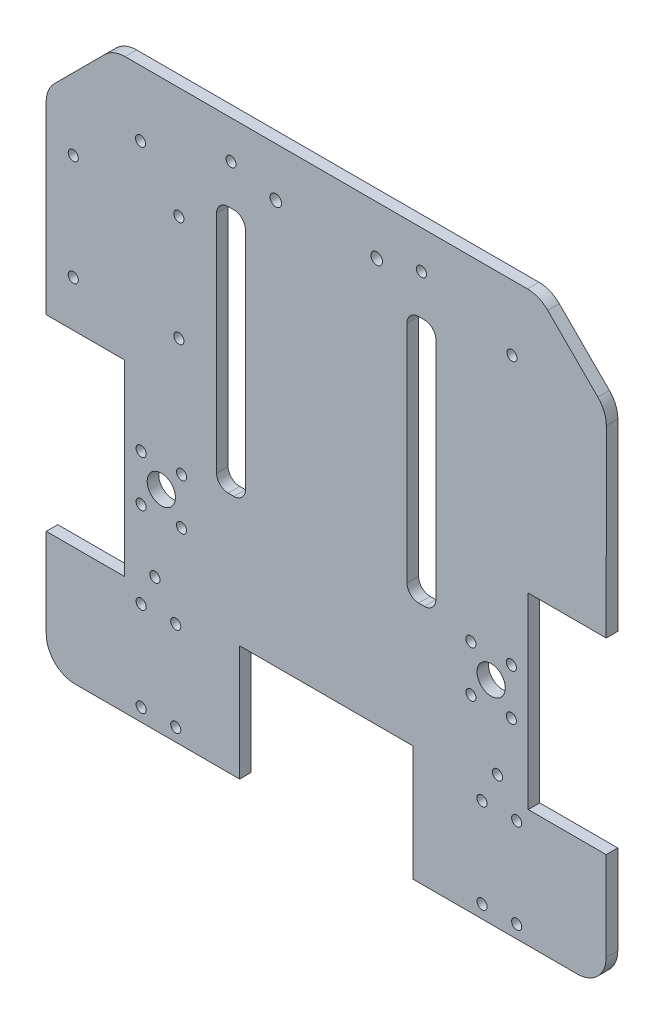
SolidWorks part; units mm, degrees
material "PMMA"
ref_plane "前视基准面" through (0, 0, 0) normal (0, 0, 1) x (1, 0, 0)
ref_plane "上视基准面" through (0, 0, 0) normal (0, 1, 0) x (1, 0, 0)
ref_plane "右视基准面" through (0, 0, 0) normal (1, 0, 0) x (0, 0, -1)
sketch "草图3" plane through (0, 0, 0) normal (0, 0, 1) x (1, 0, 0)
  line L1 (73.5057, 259.0895) -> (196.9372, 259.0895)
  line L2 (25.2215, 210.8052) -> (25.2215, 54.0895)
  line L3 (45.2215, 34.0895) -> (225.2215, 34.0895)
  line L4 (245.2215, 210.8052) -> (245.2215, 54.0895)
  line L6 (31.0793, 224.9474) -> (59.3636, 253.2316)
  line L9 (211.0793, 253.2316) -> (239.3636, 224.9474)
  arc A0 (73.5057, 259.0895) -> (59.3636, 253.2316) centre (73.5057, 239.0895) ccw
  arc A1 (211.0793, 253.2316) -> (196.9372, 259.0895) centre (196.9372, 239.0895) ccw
  arc A2 (31.0793, 224.9474) -> (25.2215, 210.8052) centre (45.2215, 210.8052) ccw
  arc A3 (25.2215, 54.0895) -> (45.2215, 34.0895) centre (45.2215, 54.0895) ccw
  arc A4 (225.2215, 34.0895) -> (245.2215, 54.0895) centre (225.2215, 54.0895) ccw
  arc A5 (245.2215, 210.8052) -> (239.3636, 224.9474) centre (225.2215, 210.8052) ccw
  dimension "D1" = 20
  dimension "D2" = 20
  dimension "D3" = 20
extrude "凸台-拉伸1" add sketch "草图3" along normal blind 4
sketch "电池槽" plane through (0, 0, 0) normal (0, 0, 1) x (1, 0, 0)
  line L0 (135.2215, 259.0895) -> (135.2215, 34.0895) construction
  line L6 (59.3636, 253.2316) -> (31.0793, 224.9474)
  line L7 (25.2215, 210.8052) -> (25.2215, 54.0895)
  line L8 (45.2215, 34.0895) -> (225.2215, 34.0895)
  line L9 (245.2215, 54.0895) -> (245.2215, 210.8052)
  line L10 (239.3636, 224.9474) -> (211.0793, 253.2316)
  line L11 (196.9372, 259.0895) -> (73.5057, 259.0895)
  line L12 (59.3636, 253.2316) -> (31.0793, 224.9474)
  line L13 (25.2215, 210.8052) -> (25.2215, 54.0895)
  line L14 (45.2215, 34.0895) -> (225.2215, 34.0895)
  line L15 (245.2215, 54.0895) -> (245.2215, 210.8052)
  line L16 (239.3636, 224.9474) -> (211.0793, 253.2316)
  line L17 (196.9372, 259.0895) -> (73.5057, 259.0895)
  line L21 (25.2215, 132.4474) -> (245.2215, 132.4474) construction
  line L22 (95.2215, 234.9474) -> (175.2215, 234.9474)
  line L24 (105.2215, 224.9474) -> (165.2215, 224.9474)
  line L25 (105.2215, 224.9474) -> (105.2215, 154.9474)
  line L26 (105.2215, 154.9474) -> (165.2215, 154.9474)
  line L27 (165.2215, 224.9474) -> (165.2215, 154.9474)
  line L28 (105.2215, 224.9474) -> (165.2215, 154.9474) construction
  line L29 (105.2215, 154.9474) -> (165.2215, 224.9474) construction
  line L30 (175.2215, 234.9474) -> (175.2215, 144.9474)
  line L31 (95.2215, 144.9474) -> (175.2215, 144.9474)
  line L32 (95.2215, 234.9474) -> (95.2215, 144.9474)
  line L33 (95.2215, 234.9474) -> (105.2215, 224.9474) construction
  line L34 (105.2215, 154.9474) -> (95.2215, 144.9474) construction
  line L35 (165.2215, 154.9474) -> (175.2215, 144.9474) construction
  line L36 (165.2215, 224.9474) -> (175.2215, 234.9474) construction
  line L37 (97.2215, 232.9474) -> (173.2215, 232.9474)
  line L38 (173.2215, 232.9474) -> (173.2215, 146.9474)
  line L39 (97.2215, 146.9474) -> (173.2215, 146.9474)
  line L40 (97.2215, 232.9474) -> (97.2215, 146.9474)
  arc A6 (73.5057, 259.0895) -> (59.3636, 253.2316) centre (73.5057, 239.0895) ccw
  arc A7 (31.0793, 224.9474) -> (25.2215, 210.8052) centre (45.2215, 210.8052) ccw
  arc A8 (25.2215, 54.0895) -> (45.2215, 34.0895) centre (45.2215, 54.0895) ccw
  arc A9 (225.2215, 34.0895) -> (245.2215, 54.0895) centre (225.2215, 54.0895) ccw
  arc A10 (245.2215, 210.8052) -> (239.3636, 224.9474) centre (225.2215, 210.8052) ccw
  arc A11 (211.0793, 253.2316) -> (196.9372, 259.0895) centre (196.9372, 239.0895) ccw
  arc A12 (73.5057, 259.0895) -> (59.3636, 253.2316) centre (73.5057, 239.0895) ccw
  arc A13 (31.0793, 224.9474) -> (25.2215, 210.8052) centre (45.2215, 210.8052) ccw
  arc A14 (25.2215, 54.0895) -> (45.2215, 34.0895) centre (45.2215, 54.0895) ccw
  arc A15 (225.2215, 34.0895) -> (245.2215, 54.0895) centre (225.2215, 54.0895) ccw
  arc A16 (245.2215, 210.8052) -> (239.3636, 224.9474) centre (225.2215, 210.8052) ccw
  arc A17 (211.0793, 253.2316) -> (196.9372, 259.0895) centre (196.9372, 239.0895) ccw
  circle A20 centre (168.2215, 227.9474) radius 1.75
  circle A21 centre (168.2215, 151.9474) radius 1.75
  circle A22 centre (102.2215, 151.9474) radius 1.75
  circle A23 centre (102.2215, 227.9474) radius 1.75
  point P18 (135.2215, 189.9474)
  dimension "D3" = 8
  dimension "D2" = 10
  dimension "D1" = 0
sketch "轮槽" plane through (0, 0, 4) normal (0, 0, 1) x (1, 0, 0)
  line L2 (235.2215, 149.9474) -> (245.2215, 149.9474)
  line L3 (235.2215, 84.9474) -> (245.2215, 84.9474)
  line L4 (205.2215, 84.9474) -> (235.2215, 84.9474)
  line L5 (25.2215, 149.9474) -> (47.2215, 149.9474)
  line L6 (59.3636, 253.2316) -> (31.0793, 224.9474)
  line L7 (25.2215, 210.8052) -> (25.2215, 54.0895)
  line L8 (45.2215, 34.0895) -> (225.2215, 34.0895)
  line L9 (245.2215, 54.0895) -> (245.2215, 210.8052)
  line L10 (239.3636, 224.9474) -> (211.0793, 253.2316)
  line L11 (196.9372, 259.0895) -> (73.5057, 259.0895)
  line L12 (59.3636, 253.2316) -> (31.0793, 224.9474) construction
  line L13 (25.2215, 210.8052) -> (25.2215, 54.0895) construction
  line L14 (45.2215, 34.0895) -> (225.2215, 34.0895) construction
  line L15 (245.2215, 54.0895) -> (245.2215, 210.8052) construction
  line L16 (239.3636, 224.9474) -> (211.0793, 253.2316) construction
  line L17 (196.9372, 259.0895) -> (73.5057, 259.0895) construction
  line L18 (47.2215, 149.9474) -> (65.2215, 149.9474)
  line L19 (65.2215, 149.9474) -> (65.2215, 84.9474)
  line L20 (65.2215, 84.9474) -> (25.2215, 84.9474)
  line L21 (205.2215, 149.9474) -> (205.2215, 84.9474)
  line L22 (235.2215, 149.9474) -> (223.2215, 149.9474)
  line L23 (223.2215, 149.9474) -> (205.2215, 149.9474)
  arc A6 (73.5057, 259.0895) -> (59.3636, 253.2316) centre (73.5057, 239.0895) ccw
  arc A7 (31.0793, 224.9474) -> (25.2215, 210.8052) centre (45.2215, 210.8052) ccw
  arc A8 (25.2215, 54.0895) -> (45.2215, 34.0895) centre (45.2215, 54.0895) ccw
  arc A9 (225.2215, 34.0895) -> (245.2215, 54.0895) centre (225.2215, 54.0895) ccw
  arc A10 (245.2215, 210.8052) -> (239.3636, 224.9474) centre (225.2215, 210.8052) ccw
  arc A11 (211.0793, 253.2316) -> (196.9372, 259.0895) centre (196.9372, 239.0895) ccw
  arc A12 (73.5057, 259.0895) -> (59.3636, 253.2316) centre (73.5057, 239.0895) ccw construction
  arc A13 (31.0793, 224.9474) -> (25.2215, 210.8052) centre (45.2215, 210.8052) ccw construction
  arc A14 (25.2215, 54.0895) -> (45.2215, 34.0895) centre (45.2215, 54.0895) ccw construction
  arc A15 (225.2215, 34.0895) -> (245.2215, 54.0895) centre (225.2215, 54.0895) ccw construction
  arc A16 (245.2215, 210.8052) -> (239.3636, 224.9474) centre (225.2215, 210.8052) ccw construction
  arc A17 (211.0793, 253.2316) -> (196.9372, 259.0895) centre (196.9372, 239.0895) ccw construction
  line M18 (25.2215, 210.8052) -> (25.2215, 54.0895)
  line M22 (245.2215, 54.0895) -> (245.2215, 210.8052)
  dimension "D1" = 0
sketch "电机" plane through (0, 0, 0) normal (0, 0, 1) x (1, 0, 0)
  line L1 (71.0715, 125.4474) -> (85.0715, 125.4474) construction
  line L7 (65.2215, 130.6974) -> (93.2215, 130.6974) construction
  line L8 (245.2215, 122.9274) -> (237.0715, 122.9274) construction
  line L9 (85.0715, 125.4474) -> (71.0715, 125.4474) construction
  line L26 (93.2215, 130.6974) -> (93.2215, 104.1974) construction
  line L27 (65.2215, 117.4474) -> (33.3715, 117.4474) construction
  line L28 (217.2215, 122.9274) -> (215.3715, 122.9274) construction
  line L29 (215.3715, 122.9274) -> (215.3715, 130.9274) construction
  line L30 (65.2215, 111.9674) -> (65.2215, 104.1974) construction
  line L31 (169.3715, 130.9274) -> (215.3715, 130.9274) construction
  line L32 (192.3715, 130.9274) -> (192.3715, 114.9274) construction
  line L33 (237.0715, 122.9274) -> (215.3715, 122.9274) construction
  line L34 (215.3715, 114.9274) -> (169.3715, 114.9274) construction
  line L35 (135.2215, 259.0895) -> (135.2215, 34.0895) construction
  line L36 (196.9372, 259.0895) -> (73.5057, 259.0895) construction
  line L37 (45.2215, 34.0895) -> (225.2215, 34.0895) construction
  line L39 (85.0715, 117.4474) -> (85.0715, 125.4474) construction
  line L40 (85.0715, 109.4474) -> (71.0715, 109.4474) construction
  line L41 (78.0715, 125.4474) -> (78.0715, 109.4474) construction
  line L44 (65.2215, 111.9674) -> (65.2215, 130.6974) construction
  line L45 (93.2215, 104.1974) -> (65.2215, 104.1974) construction
  line L51 (93.2215, 117.4474) -> (85.0715, 117.4474) construction
  line L53 (205.2215, 117.4474) -> (205.2215, 109.6774) construction
  line L63 (237.0715, 117.4474) -> (185.3715, 117.4474) construction
  line L64 (205.2215, 111.9674) -> (205.2215, 130.6974) construction
  line L65 (177.2215, 130.6974) -> (177.2215, 104.1974)
  line L66 (205.2215, 104.1974) -> (205.2215, 130.6974)
  line L67 (177.2215, 117.4474) -> (185.3715, 117.4474) construction
  line L68 (177.2215, 104.1974) -> (205.2215, 104.1974) construction
  line L69 (205.2215, 111.9674) -> (205.2215, 130.6974) construction
  line L70 (192.3715, 125.4474) -> (192.3715, 109.4474) construction
  line L71 (185.3715, 109.4474) -> (199.3715, 109.4474) construction
  line L72 (185.3715, 117.4474) -> (185.3715, 125.4474) construction
  line L73 (205.2215, 111.9674) -> (205.2215, 104.1974) construction
  line L74 (205.2215, 130.6974) -> (177.2215, 130.6974)
  line L75 (177.2215, 104.1974) -> (205.2215, 104.1974)
  line L76 (205.2215, 117.4474) -> (237.0715, 117.4474) construction
  line L77 (177.2215, 130.6974) -> (177.2215, 104.1974) construction
  line L78 (185.3715, 125.4474) -> (199.3715, 125.4474) construction
  line L79 (205.2215, 130.6974) -> (177.2215, 130.6974) construction
  line L80 (199.3715, 125.4474) -> (185.3715, 125.4474) construction
  line L81 (65.2215, 111.9674) -> (65.2215, 130.6974) construction
  line L82 (33.3715, 117.4474) -> (85.0715, 117.4474) construction
  line L83 (65.2215, 117.4474) -> (65.2215, 109.6774) construction
  line L84 (55.0715, 114.9274) -> (101.0715, 114.9274) construction
  line L85 (33.3715, 122.9274) -> (55.0715, 122.9274) construction
  line L86 (78.0715, 130.9274) -> (78.0715, 114.9274) construction
  line L87 (101.0715, 130.9274) -> (55.0715, 130.9274) construction
  line L88 (55.0715, 122.9274) -> (55.0715, 130.9274) construction
  line L89 (53.2215, 122.9274) -> (55.0715, 122.9274) construction
  line L90 (25.2215, 122.9274) -> (33.3715, 122.9274) construction
  line L91 (93.2215, 104.1974) -> (65.2215, 104.1974)
  line L92 (65.2215, 130.6974) -> (93.2215, 130.6974)
  line L93 (65.2215, 104.1974) -> (65.2215, 130.6974)
  line L94 (93.2215, 130.6974) -> (93.2215, 104.1974)
  line L95 (65.2215, 130.6974) -> (120.2215, 130.6974) construction
  line L96 (120.2215, 130.6974) -> (120.2215, 104.1974) construction
  line L97 (120.2215, 104.1974) -> (93.2215, 104.1974) construction
  circle A27 centre (185.3715, 109.4474) radius 1.75
  circle A28 centre (199.3715, 125.4474) radius 1.75
  circle A29 centre (192.3715, 117.4474) radius 4.9
  circle A30 centre (185.3715, 125.4474) radius 1.75
  circle A31 centre (199.3715, 109.4474) radius 1.75
  circle A32 centre (71.0715, 109.4474) radius 1.75
  circle A33 centre (85.0715, 125.4474) radius 1.75
  circle A34 centre (78.0715, 117.4474) radius 4.9
  circle A35 centre (71.0715, 125.4474) radius 1.75
  circle A36 centre (85.0715, 109.4474) radius 1.75
sketch "L298N" plane through (0, 0, 0) normal (0, 0, 1) x (1, 0, 0)
  line L0 (73.5057, 239.0895) -> (73.5057, 210.8052) construction
  line L1 (45.2215, 210.8052) -> (73.5057, 210.8052) construction
  line L2 (73.5057, 210.8052) -> (73.5057, 181.8052) construction
  line L3 (47.5557, 202.4552) -> (84.1557, 202.4552) construction
  line L4 (44.3557, 205.6552) -> (87.3557, 205.6552)
  line L5 (44.3557, 205.6552) -> (44.3557, 162.6552)
  line L6 (44.3557, 162.6552) -> (87.3557, 162.6552)
  line L7 (87.3557, 205.6552) -> (87.3557, 162.6552)
  line L8 (44.3557, 205.6552) -> (87.3557, 162.6552) construction
  line L9 (44.3557, 162.6552) -> (87.3557, 205.6552) construction
  line L10 (47.5557, 165.8552) -> (84.1557, 165.8552) construction
  circle A0 centre (47.5557, 165.8552) radius 1.75
  circle A2 centre (47.5557, 202.4552) radius 1.75
  circle A3 centre (84.1557, 202.4552) radius 1.75
  circle A4 centre (84.1557, 165.8552) radius 1.75
  point P6 (65.8557, 184.1552)
  point P28 (65.8557, 184.1552)
  dimension "D1" = 43
  dimension "D2" = 36.6
  dimension "D3" = 43
  dimension "D4" = 36.6
extrude "切除-拉伸5" cut sketch "L298N" along normal blind 10 contours A0 | A2 | A4 | A3
extrude "切除-拉伸7" cut sketch "电池槽" along normal blind 10
extrude "切除-拉伸8" cut sketch "轮槽" against normal blind 10 contours L20 L19 L18 L5 M18 | L22 L23 L21 L4 M22
sketch "万向轮" plane through (0, 0, 0) normal (0, 0, 1) x (1, 0, 0)
  line L0 (135.2215, 259.0895) -> (135.2215, 189.0895) construction
  line L1 (196.9372, 259.0895) -> (73.5057, 259.0895) construction
  line L2 (158.7215, 224.0895) -> (111.7215, 224.0895) construction
  line L3 (152.7215, 224.0895) -> (117.7215, 224.0895)
  line L4 (111.7215, 224.0895) -> (125.647, 235.6363)
  line L5 (158.7215, 224.0895) -> (144.796, 235.6363)
  line L6 (158.7215, 224.0895) -> (144.796, 212.5426)
  line L7 (111.7215, 224.0895) -> (125.647, 212.5426)
  circle A0 centre (117.7215, 224.0895) radius 2
  circle A1 centre (152.7215, 224.0895) radius 2
  circle A2 centre (135.2215, 224.0895) radius 13.5
  circle A3 centre (135.2215, 224.0895) radius 15
  point P7 (135.2215, 224.0895)
  point P10 (135.2215, 224.0895)
extrude "切除-拉伸10" cut sketch "万向轮" along normal blind 10
extrude "切除-拉伸3" cut sketch "电机" along normal blind 10
ref_plane "基准面1" through (0, 0, 4) normal (0, 0, 1) x (1, 0, 0)
sketch "草图11" plane through (0, 0, 4) normal (0, 0, 1) x (1, 0, 0)
  line L0 (26.7439, 218.4589) -> (243.6991, 218.4589) construction
  line L1 (65.8521, 132.7742) -> (204.5909, 132.7742) construction
  line L2 (45.2215, 34.0895) -> (225.2215, 34.0895) construction
  line L3 (204.5909, 257.5671) -> (204.5909, 34.0895) construction
  line L4 (25.2215, 54.0895) -> (245.2215, 54.0895) construction
  line L5 (73.254, 90.0895) -> (74.553, 87.8395)
  line L10 (73.4502, 218.4589) -> (72.1511, 220.7089)
  line L11 (72.1511, 220.7089) -> (69.553, 220.7089)
  line L12 (69.553, 220.7089) -> (68.254, 218.4589)
  line L13 (68.254, 218.4589) -> (69.553, 216.2089)
  line L14 (69.553, 216.2089) -> (72.1511, 216.2089)
  line L15 (72.1511, 216.2089) -> (73.4502, 218.4589)
  line L20 (77.1511, 87.8395) -> (78.4502, 90.0895)
  line L21 (77.1511, 92.3395) -> (74.553, 92.3395)
  line L22 (74.553, 87.8395) -> (77.1511, 87.8395)
  line L23 (74.553, 92.3395) -> (73.254, 90.0895)
  line L32 (78.4502, 90.0895) -> (77.1511, 92.3395)
  line L45 (65.8521, 257.5671) -> (65.8521, 34.0895) construction
  line L49 (191.9928, 90.0895) -> (193.2918, 92.3395)
  line L50 (195.8899, 92.3395) -> (197.1889, 90.0895)
  line L51 (195.8899, 87.8395) -> (193.2918, 87.8395)
  line L52 (193.2918, 92.3395) -> (195.8899, 92.3395)
  line L53 (193.2918, 87.8395) -> (191.9928, 90.0895)
  line L54 (198.2918, 216.2089) -> (196.9928, 218.4589)
  line L55 (200.8899, 216.2089) -> (198.2918, 216.2089)
  line L56 (202.1889, 218.4589) -> (200.8899, 216.2089)
  line L57 (200.8899, 220.7089) -> (202.1889, 218.4589)
  line L58 (198.2918, 220.7089) -> (200.8899, 220.7089)
  line L61 (25.2215, 84.9474) -> (25.2215, 54.0895)
  line L62 (45.2215, 34.0895) -> (225.2215, 34.0895)
  line L63 (245.2215, 54.0895) -> (245.2215, 84.9474)
  line L68 (239.3636, 224.9474) -> (211.0793, 253.2316)
  line L69 (196.9372, 259.0895) -> (73.5057, 259.0895)
  line L70 (59.3636, 253.2316) -> (31.0793, 224.9474)
  line L75 (25.2215, 84.9474) -> (25.2215, 54.0895)
  line L76 (45.2215, 34.0895) -> (225.2215, 34.0895)
  line L77 (245.2215, 54.0895) -> (245.2215, 84.9474)
  line L82 (239.3636, 224.9474) -> (211.0793, 253.2316)
  line L83 (196.9372, 259.0895) -> (73.5057, 259.0895)
  line L84 (59.3636, 253.2316) -> (31.0793, 224.9474)
  line L87 (196.9928, 218.4589) -> (198.2918, 220.7089)
  line L88 (197.1889, 90.0895) -> (195.8899, 87.8395)
  line L93 (65.2215, 149.9474) -> (65.2215, 84.9474)
  line L94 (65.2215, 149.9474) -> (65.2215, 84.9474)
  line L95 (65.2215, 84.9474) -> (25.2215, 84.9474)
  line L96 (65.2215, 84.9474) -> (25.2215, 84.9474)
  line L97 (245.2215, 84.9474) -> (205.2215, 84.9474)
  line L98 (245.2215, 84.9474) -> (205.2215, 84.9474)
  line L99 (205.2215, 84.9474) -> (205.2215, 149.9474)
  line L100 (205.2215, 84.9474) -> (205.2215, 149.9474)
  line L101 (205.2215, 149.9474) -> (245.2215, 149.9474)
  line L102 (205.2215, 149.9474) -> (245.2215, 149.9474)
  line L103 (245.2215, 149.9474) -> (245.2215, 210.8052)
  line L104 (245.2215, 149.9474) -> (245.2215, 210.8052)
  line L105 (25.2215, 210.8052) -> (25.2215, 149.9474)
  line L106 (25.2215, 210.8052) -> (25.2215, 149.9474)
  line L107 (25.2215, 149.9474) -> (65.2215, 149.9474)
  line L108 (25.2215, 149.9474) -> (65.2215, 149.9474)
  arc A0 (31.0793, 224.9474) -> (25.2215, 210.8052) centre (45.2215, 210.8052) ccw construction
  arc A1 (245.2215, 210.8052) -> (239.3636, 224.9474) centre (225.2215, 210.8052) ccw construction
  circle A2 centre (75.8521, 90.0895) radius 1.75
  arc A3 (211.0793, 253.2316) -> (196.9372, 259.0895) centre (196.9372, 239.0895) ccw construction
  arc A4 (25.2215, 54.0895) -> (45.2215, 34.0895) centre (45.2215, 54.0895) ccw construction
  circle A9 centre (70.8521, 218.4589) radius 1.75
  circle A12 centre (199.5909, 218.4589) radius 1.75
  circle A13 centre (194.5909, 90.0895) radius 1.75
  arc A18 (25.2215, 54.0895) -> (45.2215, 34.0895) centre (45.2215, 54.0895) ccw
  arc A19 (225.2215, 34.0895) -> (245.2215, 54.0895) centre (225.2215, 54.0895) ccw
  arc A20 (245.2215, 210.8052) -> (239.3636, 224.9474) centre (225.2215, 210.8052) ccw
  arc A21 (211.0793, 253.2316) -> (196.9372, 259.0895) centre (196.9372, 239.0895) ccw
  arc A22 (73.5057, 259.0895) -> (59.3636, 253.2316) centre (73.5057, 239.0895) ccw
  arc A23 (31.0793, 224.9474) -> (25.2215, 210.8052) centre (45.2215, 210.8052) ccw
  arc A24 (25.2215, 54.0895) -> (45.2215, 34.0895) centre (45.2215, 54.0895) ccw
  arc A25 (225.2215, 34.0895) -> (245.2215, 54.0895) centre (225.2215, 54.0895) ccw
  arc A26 (245.2215, 210.8052) -> (239.3636, 224.9474) centre (225.2215, 210.8052) ccw
  arc A27 (211.0793, 253.2316) -> (196.9372, 259.0895) centre (196.9372, 239.0895) ccw
  arc A28 (73.5057, 259.0895) -> (59.3636, 253.2316) centre (73.5057, 239.0895) ccw
  arc A29 (31.0793, 224.9474) -> (25.2215, 210.8052) centre (45.2215, 210.8052) ccw
  dimension "D1" = 4.5
  dimension "D3" = 36
  dimension "D2" = 0
extrude "切除-拉伸11" cut sketch "草图11" against normal up to next contours A9 | A2 | A13 | A12
ref_plane "基准面2" through (0, 0, 4) normal (0, 0, 1) x (1, 0, 0)
sketch "草图12" plane through (0, 0, 4) normal (0, 0, 1) x (1, 0, 0)
  line L0 (105.2215, 34.0895) -> (165.2215, 34.0895)
  line L1 (165.2215, -5.9105) -> (105.2215, -5.9105)
  line L2 (165.2215, -5.9105) -> (165.2215, 74.0895)
  line L3 (165.2215, 74.0895) -> (105.2215, 74.0895)
  line L4 (105.2215, -5.9105) -> (105.2215, 74.0895)
  line L5 (165.2215, -5.9105) -> (105.2215, 74.0895) construction
  line L6 (165.2215, 74.0895) -> (105.2215, -5.9105) construction
  line L7 (105.2215, 74.0895) -> (105.2215, 84.0895)
  line L8 (105.2215, 84.0895) -> (165.2215, 84.0895)
  line L9 (165.2215, 84.0895) -> (165.2215, 74.0895)
  point P0 (135.2215, 34.0895)
extrude "切除-拉伸12" cut sketch "草图12" against normal blind 10 contours L4 L0 L2 L3 | L9 L8 L7 L3
sketch "草图13" plane through (0, 0, 4) normal (0, 0, 1) x (1, 0, 0)
  line L0 (105.2215, 44.0895) -> (93.5715, 44.0895) construction
  line L1 (105.2215, 44.0895) -> (105.2215, 84.0895) construction
  line L3 (93.5715, 44.0895) -> (84.7215, 44.0895) construction
  line L4 (84.7215, 44.0895) -> (81.4215, 44.0895) construction
  line L5 (81.4215, 44.0895) -> (72.7215, 44.0895) construction
  line L6 (72.7215, 44.0895) -> (69.4215, 44.0895) construction
  line L9 (105.2215, 48.5895) -> (58.9496, 48.5895) construction
  line L10 (105.2215, 84.0895) -> (83.0715, 84.0895) construction
  line L11 (83.0715, 84.0895) -> (71.0715, 84.0895) construction
  line L12 (105.2215, 64.0895) -> (57.599, 64.0895) construction
  line L13 (165.2215, 64.0895) -> (224.665, 64.0895) construction
  line L16 (189.2215, 79.5895) -> (201.2215, 79.5895) construction
  line L17 (165.2215, 84.0895) -> (165.2215, 79.5895) construction
  line L18 (165.2215, 79.5895) -> (201.2215, 79.5895) construction
  circle A0 centre (83.0715, 48.5895) radius 1.75
  circle A1 centre (71.0715, 48.5895) radius 1.75
  circle A2 centre (71.0715, 79.5895) radius 1.75
  circle A3 centre (83.0715, 79.5895) radius 1.75
  circle A4 centre (189.2215, 79.5895) radius 1.75
  circle A5 centre (201.2215, 79.5895) radius 1.75
  circle A6 centre (201.2215, 48.5895) radius 1.75
  circle A7 centre (189.2215, 48.5895) radius 1.75
extrude "切除-拉伸14" cut sketch "草图13" against normal through all
sketch "草图14" plane through (0, 0, 4) normal (0, 0, 1) x (1, 0, 0)
  line L0 (168.2215, 207.9474) -> (163.2215, 207.9474) construction
  line L1 (163.2215, 207.9474) -> (163.2215, 213.9474) construction
  line L2 (163.2215, 213.9474) -> (167.2215, 213.9474) construction
  line L3 (167.2215, 213.9474) -> (169.2215, 213.9474)
  line L4 (173.2215, 209.9474) -> (173.2215, 131.9474)
  line L5 (169.2215, 127.9474) -> (167.2215, 127.9474)
  line L6 (163.2215, 131.9474) -> (163.2215, 209.9474)
  line L9 (107.2215, 213.9474) -> (103.2215, 213.9474) construction
  line L10 (107.2215, 207.9474) -> (107.2215, 213.9474) construction
  line L11 (107.2215, 131.9474) -> (107.2215, 209.9474)
  line L12 (101.2215, 127.9474) -> (103.2215, 127.9474)
  line L13 (97.2215, 209.9474) -> (97.2215, 131.9474)
  line L14 (103.2215, 213.9474) -> (101.2215, 213.9474)
  line L15 (97.2215, 209.9474) -> (107.2215, 209.9474) construction
  line L16 (102.2215, 207.9474) -> (102.2215, 209.9474) construction
  line L17 (168.2215, 207.9474) -> (168.2215, 209.9474) construction
  line L18 (167.2215, 209.9474) -> (169.2215, 209.9474) construction
  arc A0 (169.2215, 213.9474) -> (173.2215, 209.9474) centre (169.2215, 209.9474) cw
  arc A1 (167.2215, 127.9474) -> (163.2215, 131.9474) centre (167.2215, 131.9474) cw
  arc A2 (169.2215, 127.9474) -> (173.2215, 131.9474) centre (169.2215, 131.9474) ccw
  arc A3 (167.2215, 213.9474) -> (163.2215, 209.9474) centre (167.2215, 209.9474) ccw
  arc A4 (103.2215, 213.9474) -> (107.2215, 209.9474) centre (103.2215, 209.9474) cw
  arc A5 (101.2215, 127.9474) -> (97.2215, 131.9474) centre (101.2215, 131.9474) cw
  arc A6 (103.2215, 127.9474) -> (107.2215, 131.9474) centre (103.2215, 131.9474) ccw
  arc A7 (101.2215, 213.9474) -> (97.2215, 209.9474) centre (101.2215, 209.9474) ccw
  circle A9 centre (102.2215, 207.9474) radius 1.75
  dimension "D1" = 4
extrude "切除-拉伸15" cut sketch "草图14" against normal blind 10 contours L14 A7 L13 A5 L12 A6 L11 A4 | L3 A3 L6 A1 L5 A2 L4 A0 | A9
sketch "草图15" plane through (0, 0, 0) normal (0, 0, 1) x (1, 0, 0)
  line L0 (25.2215, 84.9474) -> (38.2215, 84.9474)
  line L2 (58.4347, 238.1606) -> (41.0816, 220.8074)
  line L12 (48.2215, 44.0895) -> (95.2215, 44.0895)
  line L13 (95.2215, 44.0895) -> (95.2215, 84.0895)
  line L14 (95.2215, 84.0895) -> (175.2215, 84.0895)
  line L15 (175.2215, 84.0895) -> (175.2215, 44.0895)
  line L16 (175.2215, 44.0895) -> (222.2215, 44.0895)
  line L22 (229.3614, 220.8074) -> (212.0083, 238.1606)
  line L23 (232.2215, 84.9474) -> (245.2215, 84.9474)
  line L30 (232.2562, 149.9474) -> (245.2215, 149.9474)
  line L32 (25.2215, 149.9474) -> (38.1867, 149.9474)
  line L35 (65.5057, 241.0895) -> (204.9372, 241.0895)
  line L63 (38.2215, 74.9474) -> (38.2215, 84.9474)
  line L64 (38.2215, 74.9474) -> (38.2215, 54.0895)
  line L79 (178.2215, 47.0895) -> (225.2215, 47.0895) construction
  line L82 (232.2215, 54.0895) -> (232.2215, 74.9474)
  line L83 (232.2215, 74.9474) -> (232.2215, 84.9474)
  line L102 (38.1867, 149.9474) -> (38.1526, 213.731)
  line L103 (232.2562, 149.9474) -> (232.2903, 213.731)
  line L105 (45.2215, 47.0895) -> (92.2215, 47.0895) construction
  line L106 (92.2215, 87.0895) -> (178.2215, 87.0895) construction
  line L114 (45.2215, 44.0895) -> (95.2215, 44.0895) construction
  line L116 (38.2215, 74.9474) -> (38.2215, 54.0895) construction
  line L118 (175.2215, 44.0895) -> (225.2215, 44.0895) construction
  line L122 (232.2215, 54.0895) -> (232.2215, 74.9474) construction
  line L145 (45.2215, 34.0895) -> (105.2215, 34.0895)
  line L150 (105.2215, 34.0895) -> (105.2215, 84.0895)
  line L151 (105.2215, 84.0895) -> (165.2215, 84.0895)
  line L152 (165.2215, 84.0895) -> (165.2215, 34.0895)
  line L153 (165.2215, 34.0895) -> (225.2215, 34.0895)
  line L158 (245.2215, 54.0895) -> (245.2215, 84.9474)
  line L159 (245.2215, 84.9474) -> (205.2215, 84.9474)
  line L160 (205.2215, 84.9474) -> (205.2215, 149.9474)
  line L162 (205.2215, 149.9474) -> (245.2215, 149.9474)
  line L172 (245.2215, 149.9474) -> (245.2215, 210.8052)
  line L173 (239.3636, 224.9474) -> (211.0793, 253.2316)
  line L180 (196.9372, 259.0895) -> (73.5057, 259.0895)
  line L181 (59.3636, 253.2316) -> (31.0793, 224.9474)
  line L190 (25.2215, 210.8052) -> (25.2215, 149.9474)
  line L191 (25.2215, 149.9474) -> (65.2215, 149.9474)
  line L192 (65.2215, 149.9474) -> (65.2215, 84.9474)
  line L193 (65.2215, 84.9474) -> (25.2215, 84.9474)
  line L194 (25.2215, 84.9474) -> (25.2215, 54.0895)
  line L200 (45.2215, 34.0895) -> (105.2215, 34.0895)
  line L204 (105.2215, 34.0895) -> (105.2215, 84.0895)
  line L205 (105.2215, 84.0895) -> (165.2215, 84.0895)
  line L206 (165.2215, 84.0895) -> (165.2215, 34.0895)
  line L207 (165.2215, 34.0895) -> (225.2215, 34.0895)
  line L212 (245.2215, 54.0895) -> (245.2215, 84.9474)
  line L220 (245.2215, 149.9474) -> (245.2215, 210.8052)
  line L221 (239.3636, 224.9474) -> (211.0793, 253.2316)
  line L222 (196.9372, 259.0895) -> (73.5057, 259.0895)
  line L223 (59.3636, 253.2316) -> (31.0793, 224.9474)
  line L228 (25.2215, 210.8052) -> (25.2215, 149.9474)
  line L236 (35.2215, 74.9474) -> (35.2215, 54.0895) construction
  line L237 (35.2215, 74.9474) -> (35.2215, 84.9474) construction
  line L238 (92.2215, 47.0895) -> (92.2215, 87.0895) construction
  line L239 (178.2215, 87.0895) -> (178.2215, 47.0895) construction
  line L240 (235.2215, 54.0895) -> (235.2215, 74.9474) construction
  line L241 (235.2215, 74.9474) -> (235.2215, 84.9474) construction
  line L242 (25.2215, 84.9474) -> (25.2215, 54.0895)
  arc A22 (204.9372, 241.0895) -> (212.0083, 238.1606) centre (204.9372, 231.0895) cw
  arc A24 (65.5057, 241.0895) -> (58.4347, 238.1606) centre (65.5057, 231.0895) ccw
  arc A27 (48.2215, 44.0895) -> (38.2215, 54.0895) centre (48.2215, 54.0895) cw
  arc A29 (222.2215, 44.0895) -> (232.2215, 54.0895) centre (222.2215, 54.0895) ccw
  arc A31 (232.2903, 213.731) -> (229.3614, 220.8074) centre (222.2903, 213.7364) ccw
  arc A45 (38.1526, 213.731) -> (41.0816, 220.8074) centre (48.1526, 213.7364) cw
  arc A69 (225.2215, 34.0895) -> (245.2215, 54.0895) centre (225.2215, 54.0895) ccw
  arc A71 (245.2215, 210.8052) -> (239.3636, 224.9474) centre (225.2215, 210.8052) ccw
  arc A73 (211.0793, 253.2316) -> (196.9372, 259.0895) centre (196.9372, 239.0895) ccw
  arc A77 (73.5057, 259.0895) -> (59.3636, 253.2316) centre (73.5057, 239.0895) ccw
  arc A81 (31.0793, 224.9474) -> (25.2215, 210.8052) centre (45.2215, 210.8052) ccw
  arc A85 (25.2215, 54.0895) -> (45.2215, 34.0895) centre (45.2215, 54.0895) ccw
  arc A89 (225.2215, 34.0895) -> (245.2215, 54.0895) centre (225.2215, 54.0895) ccw
  arc A93 (245.2215, 210.8052) -> (239.3636, 224.9474) centre (225.2215, 210.8052) ccw
  arc A95 (211.0793, 253.2316) -> (196.9372, 259.0895) centre (196.9372, 239.0895) ccw
  arc A96 (73.5057, 259.0895) -> (59.3636, 253.2316) centre (73.5057, 239.0895) ccw
  arc A97 (31.0793, 224.9474) -> (25.2215, 210.8052) centre (45.2215, 210.8052) ccw
  arc A98 (25.2215, 54.0895) -> (45.2215, 34.0895) centre (45.2215, 54.0895) ccw
  arc A115 (35.2215, 54.0895) -> (45.2215, 44.0895) centre (45.2215, 54.0895) ccw construction
  arc A116 (225.2215, 47.0895) -> (232.2215, 54.0895) centre (225.2215, 54.0895) ccw construction
  arc A117 (38.2215, 54.0895) -> (45.2215, 47.0895) centre (45.2215, 54.0895) ccw construction
  arc A118 (225.2215, 44.0895) -> (235.2215, 54.0895) centre (225.2215, 54.0895) ccw construction
  point P32 (215.2215, 149.9474)
  point P38 (65.2215, 159.9474)
  point P40 (65.2215, 74.9474)
  point P58 (55.2215, 149.9474)
  point P60 (55.2215, 84.9474)
  point P63 (205.2215, 74.9474)
  point P65 (205.2215, 159.9474)
  dimension "D2" = 10
  dimension "D6" = 10
  dimension "D1" = 0
sketch "草图16" plane through (0, 0, 0) normal (0, 0, 1) x (1, 0, 0)
  line L12 (38.1867, 149.9474) -> (38.1526, 213.731)
  line L13 (41.0816, 220.8074) -> (58.4347, 238.1606)
  line L14 (65.5057, 241.0895) -> (204.9372, 241.0895)
  line L15 (212.0083, 238.1606) -> (229.3614, 220.8074)
  line L16 (232.2903, 213.731) -> (232.2562, 149.9474)
  line L17 (232.2562, 149.9474) -> (245.2215, 149.9474)
  line L18 (245.2215, 149.9474) -> (245.2215, 210.8052)
  line L19 (239.3636, 224.9474) -> (211.0793, 253.2316)
  line L20 (196.9372, 259.0895) -> (73.5057, 259.0895)
  line L21 (59.3636, 253.2316) -> (31.0793, 224.9474)
  line L22 (25.2215, 210.8052) -> (25.2215, 149.9474)
  line L23 (25.2215, 149.9474) -> (38.1867, 149.9474)
  line L24 (38.1867, 149.9474) -> (38.1526, 213.731)
  line L25 (41.0816, 220.8074) -> (58.4347, 238.1606)
  line L26 (65.5057, 241.0895) -> (204.9372, 241.0895)
  line L27 (212.0083, 238.1606) -> (229.3614, 220.8074)
  line L28 (232.2903, 213.731) -> (232.2562, 149.9474)
  line L29 (232.2562, 149.9474) -> (245.2215, 149.9474)
  line L30 (245.2215, 149.9474) -> (245.2215, 210.8052)
  line L31 (239.3636, 224.9474) -> (211.0793, 253.2316)
  line L32 (196.9372, 259.0895) -> (73.5057, 259.0895)
  line L33 (59.3636, 253.2316) -> (31.0793, 224.9474)
  line L34 (25.2215, 210.8052) -> (25.2215, 149.9474)
  line L35 (25.2215, 149.9474) -> (38.1867, 149.9474)
  arc A8 (41.0816, 220.8074) -> (38.1526, 213.731) centre (48.1526, 213.7364) ccw
  arc A9 (65.5057, 241.0895) -> (58.4347, 238.1606) centre (65.5057, 231.0895) ccw
  arc A10 (212.0083, 238.1606) -> (204.9372, 241.0895) centre (204.9372, 231.0895) ccw
  arc A11 (232.2903, 213.731) -> (229.3614, 220.8074) centre (222.2903, 213.7364) ccw
  arc A12 (245.2215, 210.8052) -> (239.3636, 224.9474) centre (225.2215, 210.8052) ccw
  arc A13 (211.0793, 253.2316) -> (196.9372, 259.0895) centre (196.9372, 239.0895) ccw
  arc A14 (73.5057, 259.0895) -> (59.3636, 253.2316) centre (73.5057, 239.0895) ccw
  arc A15 (31.0793, 224.9474) -> (25.2215, 210.8052) centre (45.2215, 210.8052) ccw
  arc A16 (41.0816, 220.8074) -> (38.1526, 213.731) centre (48.1526, 213.7364) ccw
  arc A17 (65.5057, 241.0895) -> (58.4347, 238.1606) centre (65.5057, 231.0895) ccw
  arc A18 (212.0083, 238.1606) -> (204.9372, 241.0895) centre (204.9372, 231.0895) ccw
  arc A19 (232.2903, 213.731) -> (229.3614, 220.8074) centre (222.2903, 213.7364) ccw
  arc A20 (245.2215, 210.8052) -> (239.3636, 224.9474) centre (225.2215, 210.8052) ccw
  arc A21 (211.0793, 253.2316) -> (196.9372, 259.0895) centre (196.9372, 239.0895) ccw
  arc A22 (73.5057, 259.0895) -> (59.3636, 253.2316) centre (73.5057, 239.0895) ccw
  arc A23 (31.0793, 224.9474) -> (25.2215, 210.8052) centre (45.2215, 210.8052) ccw
  dimension "D1" = 0
extrude "切除-拉伸16" cut sketch "草图16" along normal blind 10
sketch "草图18" plane through (0, 0, 0) normal (0, 0, 1) x (1, 0, 0)
  line L0 (175.2215, 44.0895) -> (225.2215, 44.0895) construction
  line L1 (48.1867, 44.0895) -> (95.2215, 44.0895)
  line L4 (175.2215, 44.0895) -> (222.2562, 44.0895)
  line L5 (45.2215, 44.0895) -> (95.2215, 44.0895) construction
  line L6 (232.2562, 84.9474) -> (245.2215, 84.9474)
  line L8 (38.1867, 84.9474) -> (38.1867, 54.0895)
  line L10 (232.2562, 84.9474) -> (232.2562, 54.0895)
  line L11 (95.2215, 44.0895) -> (105.2215, 44.0895)
  line L12 (175.2215, 44.0895) -> (165.2215, 44.0895)
  line L14 (105.2215, 34.0895) -> (105.2215, 84.0895) construction
  line L15 (165.2215, 84.0895) -> (165.2215, 34.0895) construction
  line L18 (38.1526, 213.731) -> (38.1867, 149.9474)
  line L19 (38.1867, 149.9474) -> (65.2215, 149.9474)
  line L20 (65.2215, 149.9474) -> (65.2215, 84.9474)
  line L21 (65.2215, 84.9474) -> (25.2215, 84.9474)
  line L22 (25.2215, 84.9474) -> (25.2215, 54.0895)
  line L23 (45.2215, 34.0895) -> (105.2215, 34.0895)
  line L24 (105.2215, 34.0895) -> (105.2215, 84.0895)
  line L25 (105.2215, 84.0895) -> (165.2215, 84.0895)
  line L26 (165.2215, 84.0895) -> (165.2215, 34.0895)
  line L27 (165.2215, 34.0895) -> (225.2215, 34.0895)
  line L28 (245.2215, 54.0895) -> (245.2215, 84.9474)
  line L29 (245.2215, 84.9474) -> (205.2215, 84.9474)
  line L30 (205.2215, 84.9474) -> (205.2215, 149.9474)
  line L31 (205.2215, 149.9474) -> (232.2562, 149.9474)
  line L32 (232.2562, 149.9474) -> (232.2903, 213.731)
  line L33 (229.3614, 220.8074) -> (212.0083, 238.1606)
  line L34 (204.9372, 241.0895) -> (65.5057, 241.0895)
  line L35 (58.4347, 238.1606) -> (41.0816, 220.8074)
  line L39 (38.1867, 84.9474) -> (25.2215, 84.9474)
  line L40 (25.2215, 84.9474) -> (25.2215, 54.0895)
  line L41 (45.2215, 34.0895) -> (105.2215, 34.0895)
  line L42 (105.2215, 34.0895) -> (105.2215, 44.0895)
  line L44 (165.2215, 44.0895) -> (165.2215, 34.0895)
  line L45 (165.2215, 34.0895) -> (225.2215, 34.0895)
  line L46 (245.2215, 54.0895) -> (245.2215, 84.9474)
  line L62 (235.2215, 54.0895) -> (235.2215, 84.9474) construction
  line L63 (35.2215, 84.9474) -> (35.2215, 54.0895) construction
  line L69 (95.2215, 44.0895) -> (95.2215, 84.0895) construction
  line L70 (175.2215, 84.0895) -> (175.2215, 44.0895) construction
  arc A0 (222.2562, 44.0895) -> (232.2562, 54.0895) centre (222.2562, 54.0895) ccw
  arc A1 (48.1867, 44.0895) -> (38.1867, 54.0895) centre (48.1867, 54.0895) cw
  arc A6 (41.0816, 220.8074) -> (38.1526, 213.731) centre (48.1526, 213.7364) ccw
  arc A7 (25.2215, 54.0895) -> (45.2215, 34.0895) centre (45.2215, 54.0895) ccw
  arc A8 (225.2215, 34.0895) -> (245.2215, 54.0895) centre (225.2215, 54.0895) ccw
  arc A9 (232.2903, 213.731) -> (229.3614, 220.8074) centre (222.2903, 213.7364) ccw
  arc A10 (212.0083, 238.1606) -> (204.9372, 241.0895) centre (204.9372, 231.0895) ccw
  arc A11 (65.5057, 241.0895) -> (58.4347, 238.1606) centre (65.5057, 231.0895) ccw
  arc A13 (25.2215, 54.0895) -> (45.2215, 34.0895) centre (45.2215, 54.0895) ccw
  arc A14 (225.2215, 34.0895) -> (245.2215, 54.0895) centre (225.2215, 54.0895) ccw
  arc A20 (225.2215, 44.0895) -> (235.2215, 54.0895) centre (225.2215, 54.0895) ccw construction
  arc A21 (35.2215, 54.0895) -> (45.2215, 44.0895) centre (45.2215, 54.0895) ccw construction
  dimension "D3" = 10
  dimension "D1" = 0
  dimension "D2" = 10
extrude "切除-拉伸17" cut sketch "草图18" along normal blind 10
